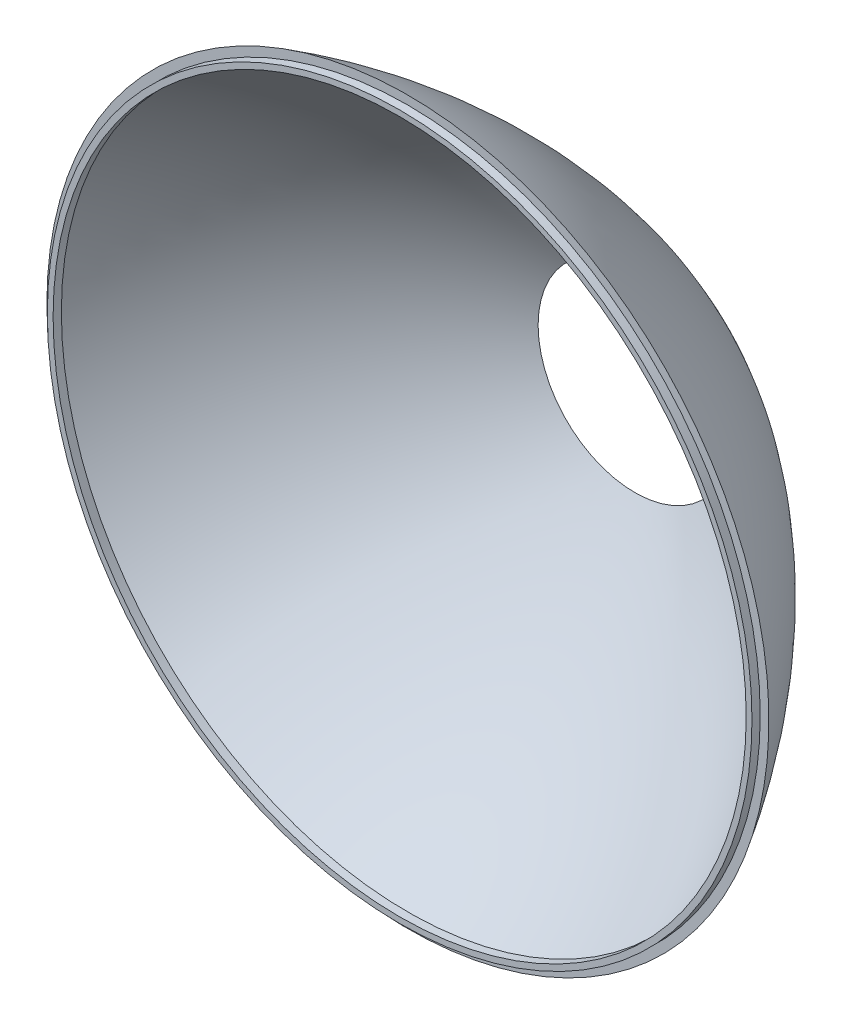
SolidWorks part; units mm, degrees
ref_plane "Front Plane" through (0, 0, 0) normal (0, 0, 1) x (1, 0, 0)
ref_plane "Top Plane" through (0, 0, 0) normal (0, 1, 0) x (1, 0, 0)
ref_plane "Right Plane" through (0, 0, 0) normal (1, 0, 0) x (0, 0, -1)
sketch "Sketch2" plane through (0, 0, 0) normal (0, 1, 0) x (1, 0, 0)
  line L0 (0, 55) -> (0, 0) construction
  line L1 (0, 0) -> (87.5, 0) construction
  line L2 (0, 55) -> (30, 55) construction
  line L3 (30, 55) -> (23.4429, 55)
  line L4 (87.5, 0) -> (83.9912, 0)
  arc A0 (30, 55) -> (87.5, 0) centre (-41.22, -77.0141) cw
  arc A1 (23.4429, 55) -> (83.9912, 0) centre (-41.22, -77.0141) cw
  arc A2 (28.5756, 52.3597) -> (84.9256, -1.5403) centre (-41.22, -77.0141) cw construction
  point P9 (25.5807, 65.5541)
  dimension "D5" = 150
  dimension "D1" = 87.5
  dimension "D2" = 30
  dimension "D4" = 55
  dimension "D3" = 3
revolve "Revolve1" add sketch "Sketch2" angle 360 about L0
sketch "Sketch4" plane through (0, 0, 0) normal (0, 0, 1) x (1, 0, 0)
  circle A0 centre (0, 0) radius 83.9912 construction
  circle A1 centre (0, 0) radius 83.9912
  circle A2 centre (0, 0) radius 85.3912
  dimension "D1" = 1.4
extrude "Boss-Extrude1" add sketch "Sketch4" along normal blind 2
